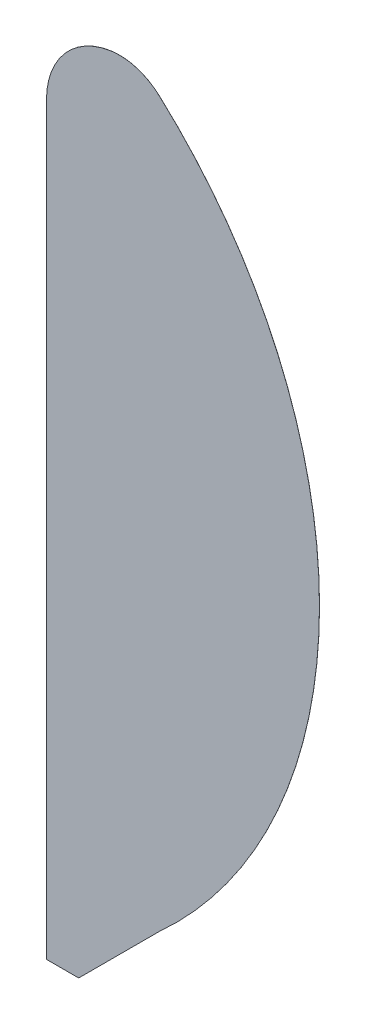
SolidWorks part; units mm, degrees
ref_plane "Front Plane" through (0, 0, 0) normal (1, 0, 0) x (0, 1, 0)
ref_plane "Top Plane" through (0, 0, 0) normal (0, 0, 1) x (0, 1, 0)
ref_plane "Right Plane" through (0, 0, 0) normal (0, 1, 0) x (-1, 0, 0)
sketch "Sketch1" plane through (0, 0, 0) normal (0, 0, 1) x (0, 1, 0)
  line L0 (0, 0) -> (0, 46433.2994) construction
  line L1 (0, 0) -> (-46433.2994, 0) construction
  line L2 (341.0561, 447.2498) -> (1519.4065, 281.6435) construction
  line L3 (0, 0) -> (115.443, 0)
  line L9 (0, 0) -> (0, -5)
  line L10 (0, -5) -> (12.5, -17.5)
  line L11 (0, 0) -> (68.604, -42.3333)
  arc A0 (115.443, 0) -> (127, -10) centre (115.443, -11.6782) cw
  arc A1 (127, -10) -> (124.708, -17.5) centre (117.9048, -11.3207) cw
  arc A2 (12.5, -17.5) -> (124.708, -17.5) centre (68.604, 33.459) ccw
  dimension "D1" = 115.443
  dimension "D2" = 5
  dimension "D3" = 42.3333
  dimension "D4" = 17.5
  dimension "Span" = 127
  dimension "D6" = 12.5
  dimension "D7" = 10
extrude "Boss-Extrude1" add sketch "Sketch1" along normal blind 0.01 contours L3 A0 A1 A2 L10 L9
equation "\"D3@Sketch1\"=\"Span@Sketch1\"/3"
equation "\"D1@Sketch1\"=\"Span@Sketch1\"*0.909"
